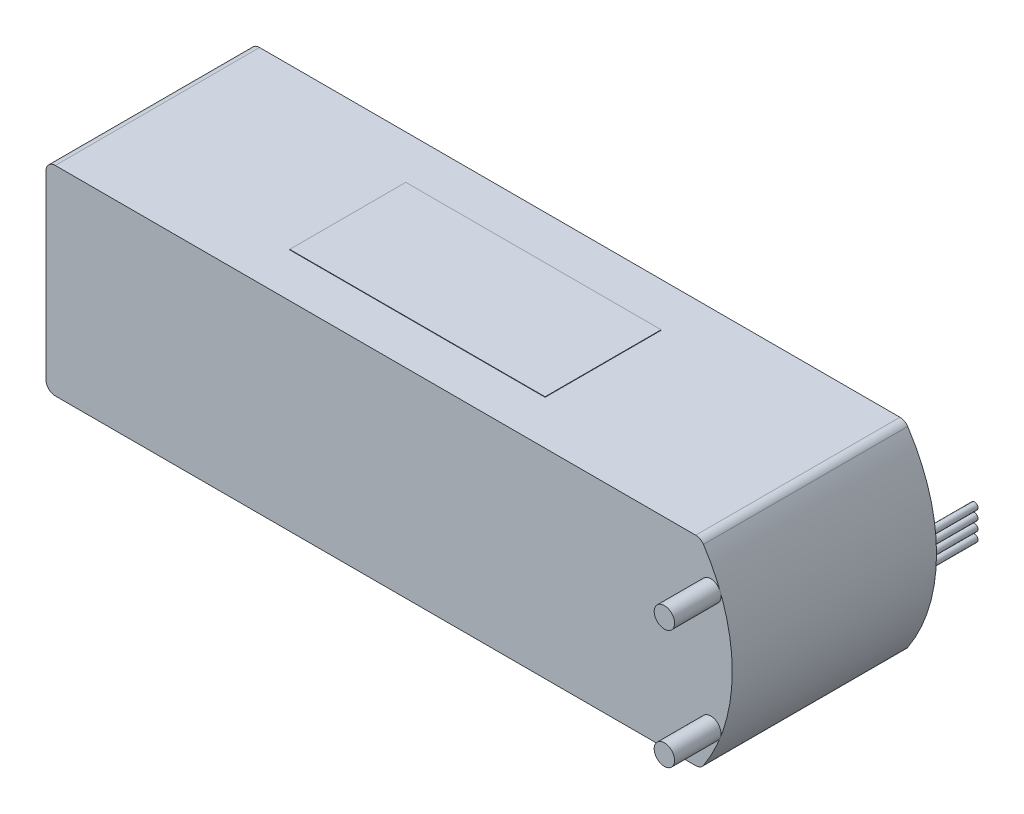
SolidWorks part; units mm, degrees
ref_plane "前视基准面" through (0, 0, 0) normal (0, 0, 1) x (1, 0, 0)
ref_plane "上视基准面" through (0, 0, 0) normal (0, 1, 0) x (1, 0, 0)
ref_plane "右视基准面" through (0, 0, 0) normal (1, 0, 0) x (0, 0, -1)
sketch "草图1" plane through (0, 0, 0) normal (0, 0, 1) x (1, 0, 0)
  line L1 (-70.5, 21.5) -> (70.5, 21.5)
  line L2 (-70.5, 21.5) -> (-70.5, -21.5)
  line L3 (-70.5, -21.5) -> (70.5, -21.5)
  line L4 (70.5, 21.5) -> (70.5, -21.5) construction
  line L5 (-70.5, 21.5) -> (70.5, -21.5) construction
  line L6 (-70.5, -21.5) -> (70.5, 21.5) construction
  arc A0 (70.5, -21.5) -> (70.5, 21.5) centre (40, 0) ccw
  point P0 (0, 0)
  dimension "D3" = 40
  dimension "D4" = 37.3162
  dimension "D1" = 141
  dimension "D2" = 43
extrude "凸台-拉伸1" add sketch "草图1" along normal mid plane 44
sketch "草图2" plane through (0, 0, 22) normal (0, 0, 1) x (1, 0, 0)
  line L0 (-5.271, 0) -> (17.0038, 0) construction
  line L1 (70.5, 21.8546) -> (70.5, -18.0902) construction
  circle A0 centre (72.7, 12.8007) radius 2.2
  circle A1 centre (72.7, -12.8007) radius 2.2
  arc A2 (70.5, -21.5) -> (70.5, 21.5) centre (40, 0) ccw construction
  dimension "D1" = 4.4
extrude "凸台-拉伸2" add sketch "草图2" along normal blind 10 separate body
sketch "草图3" plane through (0, 0, -22) normal (0, 0, -1) x (-1, 0, 0)
  line L0 (8.5368, 0) -> (-11.3095, 0) construction
  line L1 (-75.5, 10.0253) -> (-75.5, -12.4155) construction
  circle A0 centre (-75.5, 3) radius 0.75
  circle A1 centre (-75.5, 1) radius 0.75
  circle A2 centre (-75.5, -1) radius 0.75
  circle A3 centre (-75.5, -3) radius 0.75
  dimension "D1" = 1.5
  dimension "D2" = 2
  dimension "D3" = 6
  dimension "D4" = 5
extrude "凸台-拉伸3" add sketch "草图3" along normal blind 10 separate body
sketch "草图5" plane through (0, 21.5, 0) normal (0, 1, 0) x (1, 0, 0)
  line L1 (-27.5, 12.5) -> (27.5, 12.5)
  line L2 (-27.5, 12.5) -> (-27.5, -12.5)
  line L3 (-27.5, -12.5) -> (27.5, -12.5)
  line L4 (27.5, 12.5) -> (27.5, -12.5)
  line L5 (-27.5, 12.5) -> (27.5, -12.5) construction
  line L6 (-27.5, -12.5) -> (27.5, 12.5) construction
  point P0 (0, 0)
  dimension "D1" = 55
  dimension "D2" = 25
extrude "凸台-拉伸4" add sketch "草图5" along normal blind 0.1
fillet "圆角1" radius 2 4 edges at (70.5, -21.5, 0) (70.5, 21.5, 0) (-70.5, -21.5, 0) (-70.5, 21.5, 0)
